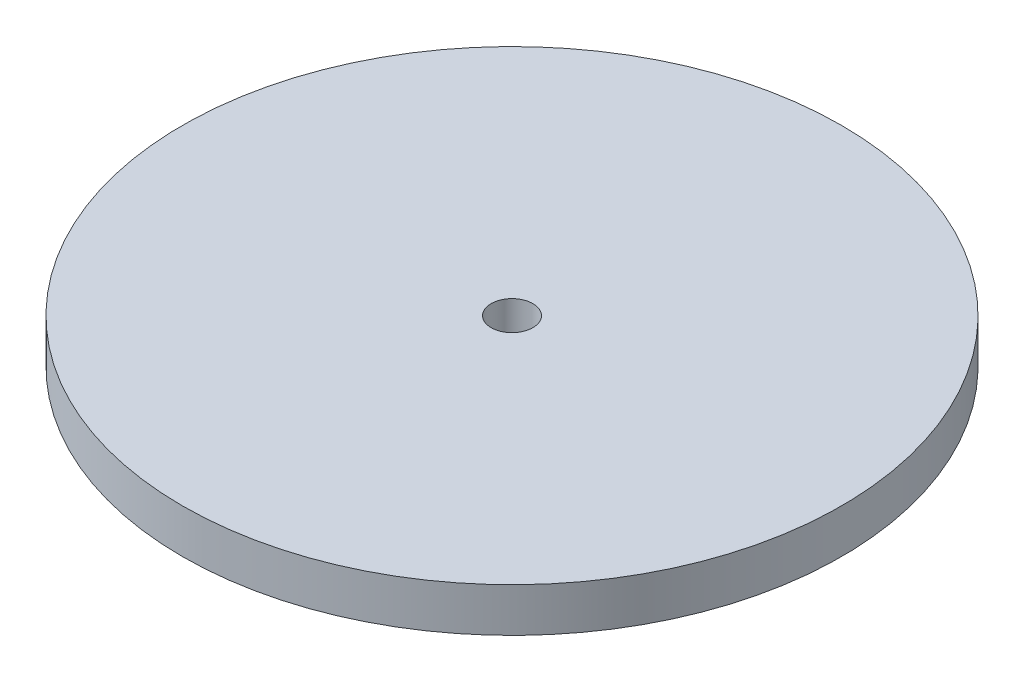
SolidWorks part; units mm, degrees
ref_plane "Front Plane" through (0, 0, 0) normal (0, 0, 1) x (1, 0, 0)
ref_plane "Top Plane" through (0, 0, 0) normal (0, 1, 0) x (1, 0, 0)
ref_plane "Right Plane" through (0, 0, 0) normal (1, 0, 0) x (0, 0, -1)
sketch "Sketch1" plane through (0, 0, 0) normal (0, 1, 0) x (1, 0, 0)
  circle A0 centre (0, 0) radius 15
  dimension "D1" = 30
extrude "Boss-Extrude1" add sketch "Sketch1" along normal blind 2
sketch "Sketch2" plane through (0, 2, 0) normal (0, 1, 0) x (1, 0, 0)
  circle A0 centre (0, 0) radius 0.95
  dimension "D1" = 1.9
extrude "Cut-Extrude1" cut sketch "Sketch2" against normal blind 2
